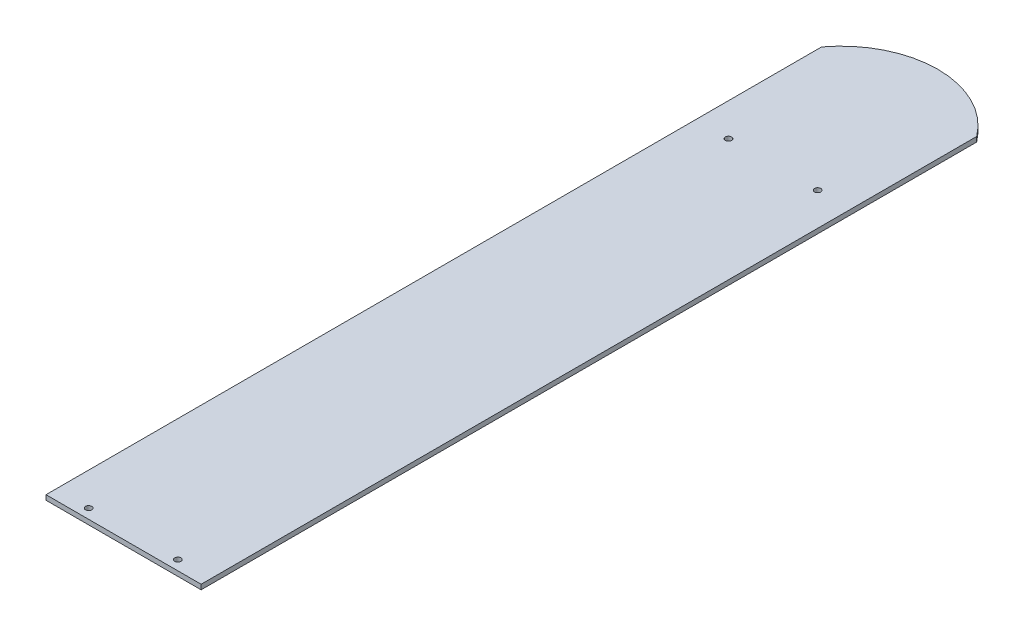
SolidWorks part; units mm, degrees
ref_plane "Front Plane" through (0, 0, 0) normal (0, 0, 1) x (1, 0, 0)
ref_plane "Top Plane" through (0, 0, 0) normal (0, 1, 0) x (1, 0, 0)
ref_plane "Right Plane" through (0, 0, 0) normal (1, 0, 0) x (0, 0, -1)
sketch "Sketch1" plane through (0, 0, 0) normal (0, 1, 0) x (1, 0, 0)
  line L2 (0, 0) -> (0, -508)
  line L3 (0, -508) -> (101.6, -508)
  line L4 (101.6, 0) -> (101.6, -508)
  arc A0 (0, 0) -> (101.6, 0) centre (50.8, -38.1) cw
  dimension "D3" = 63.5
  dimension "D1" = 508
  dimension "D2" = 101.6
extrude "Boss-Extrude1" add sketch "Sketch1" along normal blind 3.175
sketch "Sketch2" plane through (0, 0, 0) normal (0, -1, 0) x (1, 0, 0)
  line L0 (21.59, 82.55) -> (80.01, 82.55) construction
  line L1 (0, 508) -> (101.6, 508) construction
  circle A0 centre (21.59, 501.65) radius 2.032
  circle A1 centre (80.01, 501.65) radius 2.032
  circle A2 centre (21.59, 82.55) radius 2.032
  circle A3 centre (80.01, 82.55) radius 2.032
  arc A4 (0, 0) -> (101.6, 0) centre (50.8, 38.1) ccw construction
  point P11 (50.8, -25.4)
  point P12 (50.8, 82.55)
  dimension "D1" = 4.064
  dimension "D2" = 58.42
  dimension "D3" = 6.35
  dimension "D4" = 419.1
extrude "Cut-Extrude1" cut sketch "Sketch2" against normal through all
